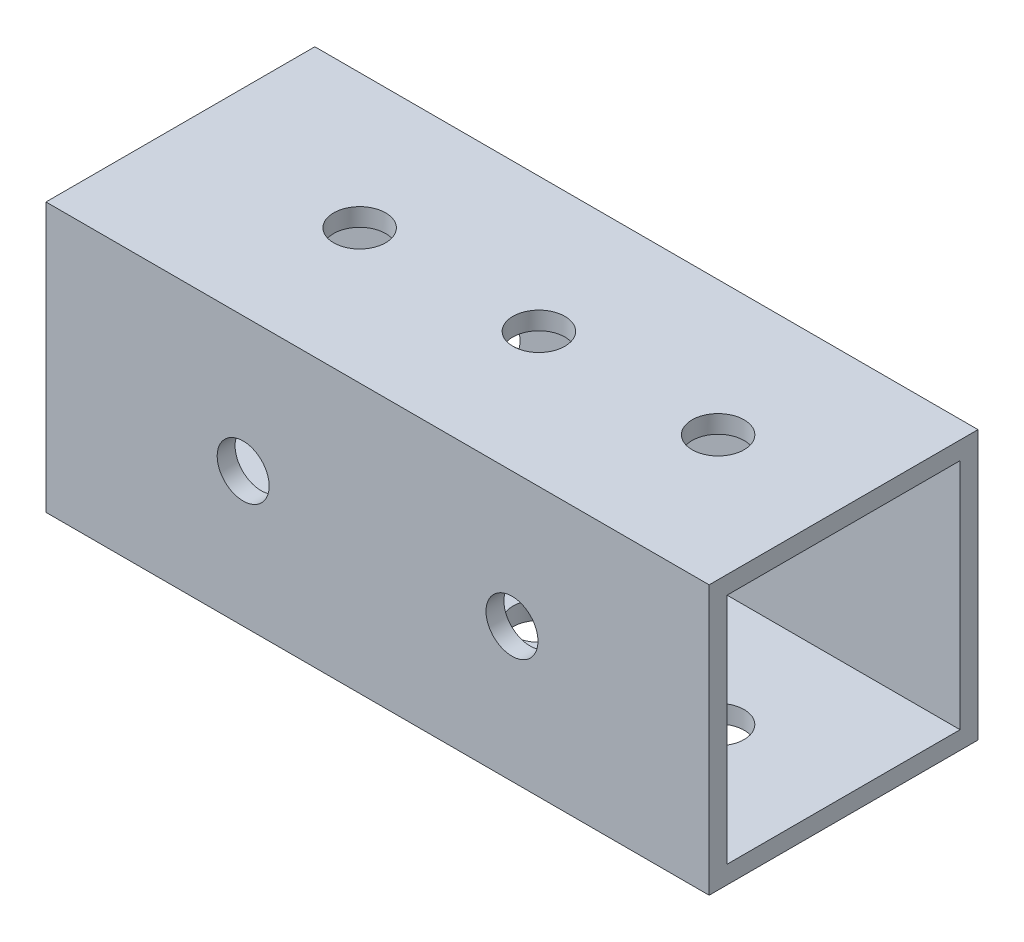
SolidWorks part; units mm, degrees
material "Thornel Mat VMA"
ref_plane "前视基准面" through (0, 0, 0) normal (0, 0, 1) x (1, 0, 0)
ref_plane "上视基准面" through (0, 0, 0) normal (0, 1, 0) x (1, 0, 0)
ref_plane "右视基准面" through (0, 0, 0) normal (1, 0, 0) x (0, 0, -1)
other "Configuration Table"
sketch "草图1" plane through (0, 0, 0) normal (1, 0, 0) x (0, 0, -1)
  line L0 (-6.5, -6.5) -> (-6.5, 6.5)
  line L1 (-7.5, -7.5) -> (7.5, -7.5)
  line L2 (-7.5, -7.5) -> (-7.5, 7.5)
  line L3 (-7.5, 7.5) -> (7.5, 7.5)
  line L4 (7.5, -7.5) -> (7.5, 7.5)
  line L5 (-7.5, -7.5) -> (7.5, 7.5) construction
  line L6 (-7.5, 7.5) -> (7.5, -7.5) construction
  line L7 (-6.5, 6.5) -> (6.5, 6.5)
  line L8 (6.5, -6.5) -> (6.5, 6.5)
  line L9 (-6.5, -6.5) -> (6.5, -6.5)
  point P0 (0, 0)
  dimension "D1" = 15
  dimension "D2" = 15
  dimension "D3" = 1
extrude "凸台-拉伸1" add sketch "草图1" along normal blind 37
sketch "草图2" plane through (0, 0, -7.5) normal (0, 0, -1) x (-1, 0, 0)
  circle A0 centre (-11, 0) radius 1.45 construction
  circle A1 centre (-26, 0) radius 1.45 construction
  circle A2 centre (-11, 0) radius 1.45
  circle A3 centre (-26, 0) radius 1.45
extrude "切除-拉伸1" cut sketch "草图2" against normal through all
sketch "草图3" plane through (0, 7.5, 0) normal (0, 1, 0) x (1, 0, 0)
  circle A0 centre (10, 0) radius 1.45 construction
  circle A1 centre (30, 0) radius 1.45 construction
  circle A2 centre (20, 0) radius 1.45 construction
  circle A3 centre (10, 0) radius 1.45
  circle A4 centre (30, 0) radius 1.45
  circle A5 centre (20, 0) radius 1.45
extrude "切除-拉伸2" cut sketch "草图3" against normal through all
